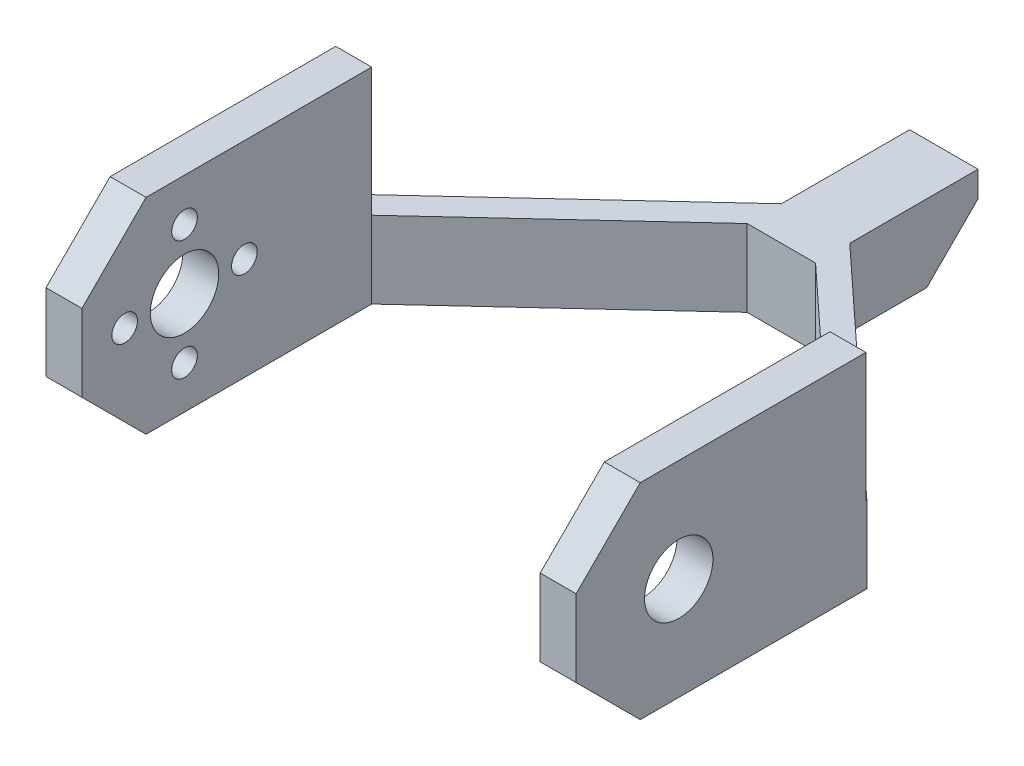
SolidWorks part; units mm, degrees
ref_plane "前视基准面" through (0, 0, 0) normal (0, 0, 1) x (1, 0, 0)
ref_plane "上视基准面" through (0, 0, 0) normal (0, 1, 0) x (1, 0, 0)
ref_plane "右视基准面" through (0, 0, 0) normal (1, 0, 0) x (0, 0, -1)
sketch "Sketch1" plane through (0, 0, 0) normal (1, 0, 0) x (0, 0, -1)
  line L0 (-12, 12) -> (-12, -12)
  line L1 (-12, 12) -> (12, 12)
  line L3 (12, 12) -> (12, -12) construction
  line L5 (-12, -12) -> (12, -12)
  line L6 (12, -12) -> (47, -12)
  line L7 (47, 12) -> (12, 12)
  line L8 (12, 12) -> (-12, -12) construction
  line L9 (47, 12) -> (47, -12)
  dimension "D1" = 24
  dimension "D2" = 47
extrude "Boss-Extrude1" add sketch "Sketch1" against normal blind 62
sketch "Sketch2" plane through (0, 12, 0) normal (0, 1, 0) x (1, 0, 0)
  line L0 (-57.8, -12) -> (-57.8, 21.8889)
  line L1 (-35, 47) -> (-27, 47) construction
  line L2 (-62, 47) -> (-62, -12) construction
  line L3 (-57.8, -12) -> (-4.2, -12) construction
  line L4 (0, 47) -> (0, -12) construction
  line L5 (-62, 22) -> (-62, 47)
  line L6 (-4.2, 21.8889) -> (-4.2, -12)
  line L7 (-4.2, -12) -> (-57.8, -12)
  line L8 (-27, 43) -> (-4.2, 21.8889)
  line L9 (-62, 47) -> (-35, 47)
  line L10 (-35, 43) -> (-27, 43)
  line L11 (-27, 47) -> (0, 47)
  line L12 (-27, 47) -> (0, 22)
  line L13 (0, 47) -> (0, 22)
  line L15 (-31, 47) -> (-31, 43) construction
  line L16 (-35, 43) -> (-57.8, 21.8889)
  line L17 (-35, 47) -> (-62, 22)
  line L20 (-62, -12) -> (0, -12) construction
  line L21 (-62, 47) -> (0, 47) construction
  line L22 (0, 47) -> (0, -12) construction
  line L23 (-62, 47) -> (-62, -12) construction
  dimension "D1" = 4
  dimension "D2" = 25
  dimension "D3" = 4.2
  dimension "D4" = 4.2
  dimension "D5" = 8
extrude "Cut-Extrude1" cut sketch "Sketch2" against normal up to next
sketch "Sketch9" plane through (0, 12, 0) normal (0, 1, 0) x (1, 0, 0)
  line L1 (-35, 47) -> (-27, 47)
  line L2 (-35, 47) -> (-35, 62)
  line L3 (-35, 62) -> (-27, 62)
  line L4 (-27, 47) -> (-27, 62)
  dimension "D1" = 15
extrude "Boss-Extrude2" add sketch "Sketch9" against normal up to surface (9 mm away) from offset 15 up to face at (-31, -12, -18.3148) offset against normal yes
sketch "Sketch7" plane through (0, 0, 0) normal (1, 0, 0) x (0, 0, -1)
  circle A0 centre (0, 0) radius 4
extrude "Cut-Extrude4" cut sketch "Sketch7" against normal blind 70
sketch "Sketch8" plane through (-62, 0, 0) normal (-1, 0, 0) x (0, 0, 1)
  line L0 (0, 0) -> (0, 7) construction
  circle A0 centre (0, 7) radius 1.5
  circle A1 centre (7, 0) radius 1.5
  circle A2 centre (0, -7) radius 1.5
  circle A3 centre (-7, 0) radius 1.5
  point P13 (0, 0)
extrude "Cut-Extrude5" cut sketch "Sketch8" against normal up to next
chamfer "Chamfer1" distance 7.5 angle 45 4 edges at (-2.1, -12, 12) (-59.9, -12, 12) (-2.1, 12, 12) (-59.9, 12, 12)
sketch "Sketch10" plane through (0, 12, 0) normal (0, 1, 0) x (1, 0, 0)
  line L0 (-62, 22) -> (-35, 47) construction
  line L1 (-35, 47) -> (-27, 47) construction
  line L2 (-27, 47) -> (0, 22) construction
  line L3 (-4.2, 21.8889) -> (-27, 43) construction
  line L4 (-27, 43) -> (-35, 43) construction
  line L5 (-35, 43) -> (-57.8, 21.8889) construction
  line L6 (-62, 22) -> (-35, 47)
  line L7 (-35, 47) -> (-27, 47)
  line L8 (-27, 47) -> (0, 22)
  line L9 (-4.2, 21.8889) -> (-27, 43)
  line L10 (-27, 43) -> (-35, 43)
  line L11 (-35, 43) -> (-57.8, 21.8889)
  line L12 (-57.8, 21.8889) -> (-62, 21.8889)
  line L13 (-62, 22) -> (-62, -4.5) construction
  line L14 (-62, 21.8889) -> (-62, 22)
  line L15 (-4.2, 21.8889) -> (0, 21.8889)
  line L16 (0, 22) -> (0, -4.5) construction
  line L17 (0, 21.8889) -> (0, 22)
extrude "Cut-Extrude6" cut sketch "Sketch10" against normal up to surface (15 mm away) up to face at (-32, -3, -54.5)
chamfer "Chamfer2" distance 6 angle 45 1 edges at (-31, -12, -62)
